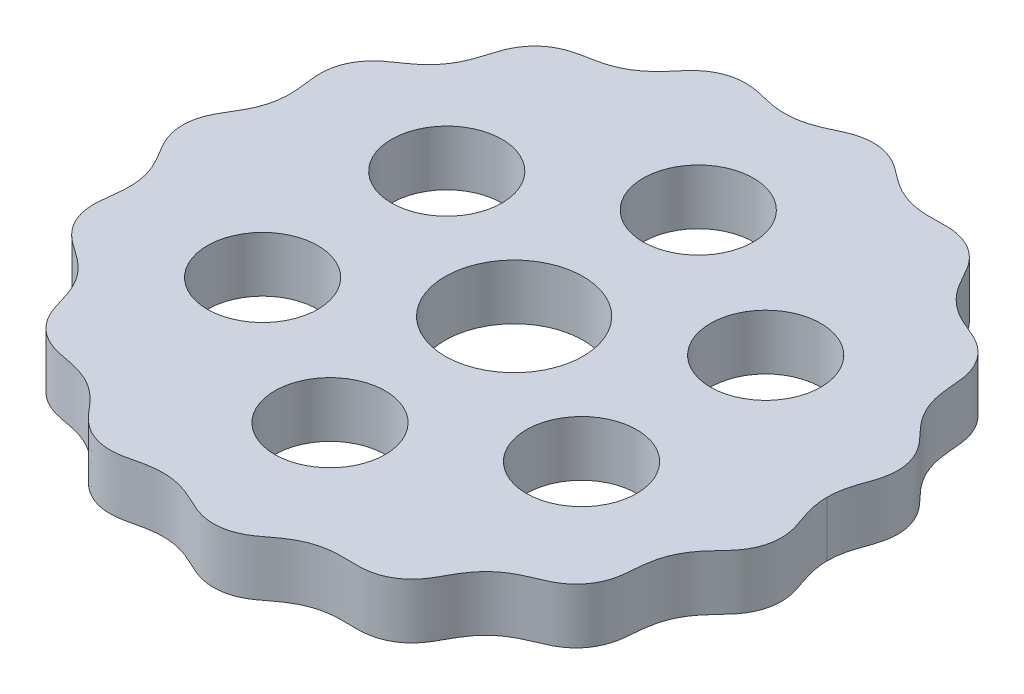
SolidWorks part; units mm, degrees
ref_plane "Front Plane" through (0, 0, 0) normal (0, 0, 1) x (1, 0, 0)
ref_plane "Top Plane" through (0, 0, 0) normal (0, 1, 0) x (1, 0, 0)
ref_plane "Right Plane" through (0, 0, 0) normal (1, 0, 0) x (0, 0, -1)
sketch "Sketch3" plane through (0, 0, 0) normal (0, 1, 0) x (1, 0, 0)
  line L0 (-55, 0) -> (55, 0) construction
  spline S0 degree 4 poles (35.4019, 9.4247) (35.4983, 9.2764) (35.6802, 8.9725) (35.9124, 8.5032) (36.141, 7.8495) (36.2863, 7.1812) (36.3494, 6.5087) (36.3306, 5.7798) (36.2114, 5.0053) (36.0004, 4.261) (35.7443, 3.5425) (35.5113, 2.8825) (35.3211, 2.2743) (35.1853, 1.7286) (35.1041, 1.291) (35.0594, 0.9663) (35.0365, 0.757) (35.0218, 0.5885) (35.0108, 0.4219) (35.0034, 0.2569) (34.9997, 0.0577) (34.9997, -0.0577) (35.0034, -0.2568) (35.0108, -0.4216) (35.0218, -0.5882) (35.0365, -0.7567) (35.0593, -0.9658) (35.104, -1.2906) (35.1852, -1.7284) (35.3211, -2.2743) (35.5114, -2.8829) (35.7441, -3.5419) (35.9992, -4.258) (36.256, -5.1614) (36.3903, -6.2748) (36.277, -7.5121) (35.8687, -8.6952) (35.2773, -9.6694) (34.5543, -10.5199) (33.7836, -11.2989) (32.9858, -12.2016) (32.2646, -13.303) (31.7377, -14.5286) (31.4262, -15.8454) (31.2991, -17.2726) (31.2161, -18.7053) (30.8161, -20.1006) (30.0732, -21.3418) (29.1744, -22.2504) (28.1724, -22.8961) (27.1276, -23.3559) (26.1086, -23.7587) (25.0498, -24.278) (23.9897, -24.9979) (23.0387, -25.9222) (22.2349, -27.0329) (21.57, -28.2819) (20.9001, -29.5134) (19.9625, -30.5741) (18.7952, -31.3663) (17.5956, -31.8107) (16.4147, -31.9743) (15.2812, -31.959) (14.2035, -31.9175) (13.0422, -31.968) (11.7833, -32.2012) (10.5313, -32.6697) (9.484, -33.2925) (8.6483, -33.9206) (7.824, -34.5602) (6.9633, -35.1551) (5.8447, -35.655) (4.4715, -35.8938) (3.1871, -35.8055) (2.026, -35.4617) (0.9923, -34.9762) (0.0227, -34.5029) (-1.0531, -34.0876) (-2.2996, -33.7945) (-3.6433, -33.7224) (-5.0385, -33.8989) (-6.246, -34.2125) (-7.2644, -34.4441) (-8.3052, -34.5433) (-9.3521, -34.4822) (-10.5168, -34.1673) (-11.6593, -33.5372) (-12.5907, -32.7091) (-13.341, -31.8149) (-14.0543, -30.9824) (-14.885, -30.183) (-15.9219, -29.4318) (-16.9904, -28.9178) (-18.0263, -28.6023) (-18.918, -28.4136) (-19.5788, -28.294) (-20.4038, -28.1355) (-21.3777, -27.8617) (-22.444, -27.3351) (-23.4837, -26.4602) (-24.2541, -25.4059) (-24.7506, -24.2626) (-25.0639, -23.1466) (-25.3786, -22.114) (-25.8131, -21.0649) (-26.4604, -19.9607) (-27.3438, -18.9326) (-28.3229, -18.1436) (-29.2182, -17.5418) (-30.0287, -16.9727) (-30.7971, -16.3286) (-31.5499, -15.4136) (-32.138, -14.1887) (-32.4089, -12.902) (-32.389, -11.6377) (-32.2136, -10.4744) (-32.0853, -9.3852) (-32.0701, -8.4106) (-32.1519, -7.5639) (-32.3146, -6.756) (-32.5488, -5.9926) (-32.8579, -5.2665) (-33.2246, -4.5794) (-33.5887, -3.9735) (-33.9236, -3.4333) (-34.2476, -2.8753) (-34.5352, -2.2866) (-34.722, -1.7814) (-34.8335, -1.3753) (-34.8947, -1.0872) (-34.9248, -0.9216) (-34.9499, -0.7552) (-34.9676, -0.6083) (-34.9796, -0.4838) (-34.9875, -0.3802) (-34.9925, -0.2949) (-34.9973, -0.1832) (-35.0004, -0.0424) (-35.0004, 0.0431) (-34.9972, 0.1843) (-34.9924, 0.2965) (-34.9873, 0.3822) (-34.9793, 0.4864) (-34.9672, 0.6115) (-34.9494, 0.7593) (-34.924, 0.9265) (-34.8935, 1.0929) (-34.8494, 1.2998) (-34.7866, 1.5457) (-34.6996, 1.8289) (-34.5822, 2.1464) (-34.4186, 2.5258) (-34.1982, 2.9612) (-33.9151, 3.4472) (-33.5795, 3.9884) (-33.2182, 4.5907) (-32.8574, 5.269) (-32.552, 5.9859) (-32.319, 6.7399) (-32.1567, 7.5336) (-32.0735, 8.3613) (-32.079, 9.0238) (-32.1147, 9.5145) (-32.1382, 9.7593) knots 0 0 0 0 0 0.005235 0.01047 0.015454 0.020438 0.025422 0.030406 0.03698 0.043555 0.048266 0.052978 0.057689 0.062401 0.064893 0.066139 0.067385 0.068631 0.069877 0.071123 0.07237 0.073615 0.074861 0.076106 0.077352 0.078597 0.079843 0.082334 0.087049 0.091763 0.096478 0.101193 0.107725 0.114257 0.124215 0.134174 0.144133 0.15093 0.157727 0.167143 0.176558 0.186521 0.196482 0.206428 0.216375 0.228908 0.238867 0.248826 0.258784 0.266347 0.27391 0.282559 0.291208 0.301173 0.311645 0.3216 0.331555 0.343059 0.353018 0.362977 0.372935 0.380513 0.388091 0.396475 0.404859 0.414823 0.425824 0.43578 0.440758 0.445737 0.45671 0.466668 0.476627 0.486585 0.494428 0.502271 0.510391 0.51851 0.528475 0.540003 0.54996 0.559918 0.565389 0.570861 0.580819 0.590778 0.600736 0.609095 0.617453 0.625308 0.633162 0.643126 0.655188 0.660155 0.665121 0.670088 0.675054 0.685012 0.69497 0.704929 0.714887 0.72326 0.731632 0.739222 0.746812 0.756777 0.769366 0.779036 0.78387 0.788705 0.798662 0.808621 0.81858 0.828538 0.837175 0.845812 0.853389 0.860965 0.865947 0.870929 0.877739 0.88455 0.889251 0.893953 0.898654 0.903356 0.908335 0.913314 0.914559 0.915803 0.917048 0.918293 0.919538 0.92016 0.920783 0.921405 0.922028 0.923272 0.924524 0.92515 0.925775 0.926401 0.927027 0.928278 0.92953 0.930781 0.932033 0.933284 0.935787 0.93829 0.940793 0.943295 0.948006 0.952717 0.957428 0.962139 0.968786 0.975432 0.98044 0.985447 0.992723 1 1 1 1 1 construction
  spline S1 degree 4 poles (35, 0) (35, -0.0358) (35.0006, -0.1075) (35.0034, -0.2568) (35.0108, -0.4216) (35.0218, -0.5882) (35.0365, -0.7567) (35.0593, -0.9658) (35.104, -1.2906) (35.1852, -1.7284) (35.3211, -2.2743) (35.5114, -2.8829) (35.7441, -3.5419) (35.9992, -4.258) (36.256, -5.1614) (36.3903, -6.2748) (36.277, -7.5121) (35.8687, -8.6952) (35.2773, -9.6694) (34.5543, -10.5199) (33.7836, -11.2989) (32.9858, -12.2016) (32.2646, -13.303) (31.7377, -14.5286) (31.4262, -15.8454) (31.2991, -17.2726) (31.2161, -18.7053) (30.8161, -20.1006) (30.0732, -21.3418) (29.1744, -22.2504) (28.1724, -22.8961) (27.1276, -23.3559) (26.1086, -23.7587) (25.0498, -24.278) (23.9897, -24.9979) (23.0387, -25.9222) (22.2349, -27.0329) (21.57, -28.2819) (20.9001, -29.5134) (19.9625, -30.5741) (18.7952, -31.3663) (17.5956, -31.8107) (16.4147, -31.9743) (15.2812, -31.959) (14.2035, -31.9175) (13.0422, -31.968) (11.7833, -32.2012) (10.5313, -32.6697) (9.484, -33.2925) (8.6483, -33.9206) (7.824, -34.5602) (6.9633, -35.1551) (5.8447, -35.655) (4.4715, -35.8938) (3.1871, -35.8055) (2.026, -35.4617) (0.9923, -34.9762) (0.0227, -34.5029) (-1.0531, -34.0876) (-2.2996, -33.7945) (-3.6433, -33.7224) (-5.0385, -33.8989) (-6.246, -34.2125) (-7.2644, -34.4441) (-8.3052, -34.5433) (-9.3521, -34.4822) (-10.5168, -34.1673) (-11.6593, -33.5372) (-12.5907, -32.7091) (-13.341, -31.8149) (-14.0543, -30.9824) (-14.885, -30.183) (-15.9219, -29.4318) (-16.9904, -28.9178) (-18.0263, -28.6023) (-18.918, -28.4136) (-19.5788, -28.294) (-20.4038, -28.1355) (-21.3777, -27.8617) (-22.444, -27.3351) (-23.4837, -26.4602) (-24.2541, -25.4059) (-24.7506, -24.2626) (-25.0639, -23.1466) (-25.3786, -22.114) (-25.8131, -21.0649) (-26.4604, -19.9607) (-27.3438, -18.9326) (-28.3229, -18.1436) (-29.2182, -17.5418) (-30.0287, -16.9727) (-30.7971, -16.3286) (-31.5499, -15.4136) (-32.138, -14.1887) (-32.4089, -12.902) (-32.389, -11.6377) (-32.2136, -10.4744) (-32.0853, -9.3852) (-32.0701, -8.4106) (-32.1519, -7.5639) (-32.3146, -6.756) (-32.5488, -5.9926) (-32.8579, -5.2665) (-33.2246, -4.5794) (-33.5887, -3.9735) (-33.9236, -3.4333) (-34.2476, -2.8753) (-34.5352, -2.2866) (-34.722, -1.7814) (-34.8335, -1.3753) (-34.8947, -1.0872) (-34.9248, -0.9216) (-34.9499, -0.7552) (-34.9676, -0.6083) (-34.9796, -0.4838) (-34.9875, -0.3802) (-34.9925, -0.2949) (-34.9973, -0.1832) (-34.9994, -0.0895) (-35, -0.0358) (-35, 0) knots 0.07237 0.07237 0.07237 0.07237 0.07237 0.073615 0.074861 0.076106 0.077352 0.078597 0.079843 0.082334 0.087049 0.091763 0.096478 0.101193 0.107725 0.114257 0.124215 0.134174 0.144133 0.15093 0.157727 0.167143 0.176558 0.186521 0.196482 0.206428 0.216375 0.228908 0.238867 0.248826 0.258784 0.266347 0.27391 0.282559 0.291208 0.301173 0.311645 0.3216 0.331555 0.343059 0.353018 0.362977 0.372935 0.380513 0.388091 0.396475 0.404859 0.414823 0.425824 0.43578 0.440758 0.445737 0.45671 0.466668 0.476627 0.486585 0.494428 0.502271 0.510391 0.51851 0.528475 0.540003 0.54996 0.559918 0.565389 0.570861 0.580819 0.590778 0.600736 0.609095 0.617453 0.625308 0.633162 0.643126 0.655188 0.660155 0.665121 0.670088 0.675054 0.685012 0.69497 0.704929 0.714887 0.72326 0.731632 0.739222 0.746812 0.756777 0.769366 0.779036 0.78387 0.788705 0.798662 0.808621 0.81858 0.828538 0.837175 0.845812 0.853389 0.860965 0.865947 0.870929 0.877739 0.88455 0.889251 0.893953 0.898654 0.903356 0.908335 0.913314 0.914559 0.915803 0.917048 0.918293 0.919538 0.92016 0.920783 0.921405 0.922028 0.923272 0.923272 0.923272 0.923272 0.923272
  spline S2 degree 4 poles (35, 0) (35, 0.0358) (35.0006, 0.1075) (35.0034, 0.2568) (35.0108, 0.4216) (35.0218, 0.5882) (35.0365, 0.7567) (35.0593, 0.9658) (35.104, 1.2906) (35.1852, 1.7284) (35.3211, 2.2743) (35.5114, 2.8829) (35.7441, 3.5419) (35.9992, 4.258) (36.256, 5.1614) (36.3903, 6.2748) (36.277, 7.5121) (35.8687, 8.6952) (35.2773, 9.6694) (34.5543, 10.5199) (33.7836, 11.2989) (32.9858, 12.2016) (32.2646, 13.303) (31.7377, 14.5286) (31.4262, 15.8454) (31.2991, 17.2726) (31.2161, 18.7053) (30.8161, 20.1006) (30.0732, 21.3418) (29.1744, 22.2504) (28.1724, 22.8961) (27.1276, 23.3559) (26.1086, 23.7587) (25.0498, 24.278) (23.9897, 24.9979) (23.0387, 25.9222) (22.2349, 27.0329) (21.57, 28.2819) (20.9001, 29.5134) (19.9625, 30.5741) (18.7952, 31.3663) (17.5956, 31.8107) (16.4147, 31.9743) (15.2812, 31.959) (14.2035, 31.9175) (13.0422, 31.968) (11.7833, 32.2012) (10.5313, 32.6697) (9.484, 33.2925) (8.6483, 33.9206) (7.824, 34.5602) (6.9633, 35.1551) (5.8447, 35.655) (4.4715, 35.8938) (3.1871, 35.8055) (2.026, 35.4617) (0.9923, 34.9762) (0.0227, 34.5029) (-1.0531, 34.0876) (-2.2996, 33.7945) (-3.6433, 33.7224) (-5.0385, 33.8989) (-6.246, 34.2125) (-7.2644, 34.4441) (-8.3052, 34.5433) (-9.3521, 34.4822) (-10.5168, 34.1673) (-11.6593, 33.5372) (-12.5907, 32.7091) (-13.341, 31.8149) (-14.0543, 30.9824) (-14.885, 30.183) (-15.9219, 29.4318) (-16.9904, 28.9178) (-18.0263, 28.6023) (-18.918, 28.4136) (-19.5788, 28.294) (-20.4038, 28.1355) (-21.3777, 27.8617) (-22.444, 27.3351) (-23.4837, 26.4602) (-24.2541, 25.4059) (-24.7506, 24.2626) (-25.0639, 23.1466) (-25.3786, 22.114) (-25.8131, 21.0649) (-26.4604, 19.9607) (-27.3438, 18.9326) (-28.3229, 18.1436) (-29.2182, 17.5418) (-30.0287, 16.9727) (-30.7971, 16.3286) (-31.5499, 15.4136) (-32.138, 14.1887) (-32.4089, 12.902) (-32.389, 11.6377) (-32.2136, 10.4744) (-32.0853, 9.3852) (-32.0701, 8.4106) (-32.1519, 7.5639) (-32.3146, 6.756) (-32.5488, 5.9926) (-32.8579, 5.2665) (-33.2246, 4.5794) (-33.5887, 3.9735) (-33.9236, 3.4333) (-34.2476, 2.8753) (-34.5352, 2.2866) (-34.722, 1.7814) (-34.8335, 1.3753) (-34.8947, 1.0872) (-34.9248, 0.9216) (-34.9499, 0.7552) (-34.9676, 0.6083) (-34.9796, 0.4838) (-34.9875, 0.3802) (-34.9925, 0.2949) (-34.9973, 0.1832) (-34.9994, 0.0895) (-35, 0.0358) (-35, 0) knots 0.07237 0.07237 0.07237 0.07237 0.07237 0.073615 0.074861 0.076106 0.077352 0.078597 0.079843 0.082334 0.087049 0.091763 0.096478 0.101193 0.107725 0.114257 0.124215 0.134174 0.144133 0.15093 0.157727 0.167143 0.176558 0.186521 0.196482 0.206428 0.216375 0.228908 0.238867 0.248826 0.258784 0.266347 0.27391 0.282559 0.291208 0.301173 0.311645 0.3216 0.331555 0.343059 0.353018 0.362977 0.372935 0.380513 0.388091 0.396475 0.404859 0.414823 0.425824 0.43578 0.440758 0.445737 0.45671 0.466668 0.476627 0.486585 0.494428 0.502271 0.510391 0.51851 0.528475 0.540003 0.54996 0.559918 0.565389 0.570861 0.580819 0.590778 0.600736 0.609095 0.617453 0.625308 0.633162 0.643126 0.655188 0.660155 0.665121 0.670088 0.675054 0.685012 0.69497 0.704929 0.714887 0.72326 0.731632 0.739222 0.746812 0.756777 0.769366 0.779036 0.78387 0.788705 0.798662 0.808621 0.81858 0.828538 0.837175 0.845812 0.853389 0.860965 0.865947 0.870929 0.877739 0.88455 0.889251 0.893953 0.898654 0.903356 0.908335 0.913314 0.914559 0.915803 0.917048 0.918293 0.919538 0.92016 0.920783 0.921405 0.922028 0.923272 0.923272 0.923272 0.923272 0.923272
  point P0 (-104.1334, 36.8865)
extrude "Boss-Extrude1" add sketch "Sketch3" along normal blind 6
sketch "Sketch4" plane through (0, 6, 0) normal (0, 1, 0) x (1, 0, 0)
  circle A0 centre (1, 0) radius 7.5
  circle A1 centre (1, 0) radius 20 construction
  circle A2 centre (1, 20) radius 6
  circle A3 centre (18.3205, 10) radius 6
  circle A4 centre (18.3205, -10) radius 6
  circle A5 centre (1, -20) radius 6
  circle A6 centre (-16.3205, -10) radius 6
  circle A7 centre (-16.3205, 10) radius 6
  point P6 (0, 0)
  point P19 (1, 0)
  dimension "D1" = 15
  dimension "D2" = 40
  dimension "D3" = 12
  dimension "D5" = 1
  dimension "D4" = 6
extrude "Cut-Extrude1" cut sketch "Sketch4" against normal through all
equation "\"R_SUN\"= 40"
equation "\"R_ROLL\"= 5"
equation "\"GRATIO\"= 15"
equation "\"RHO\"= 1"
equation "\"D5@Sketch4\"=\"RHO\""
